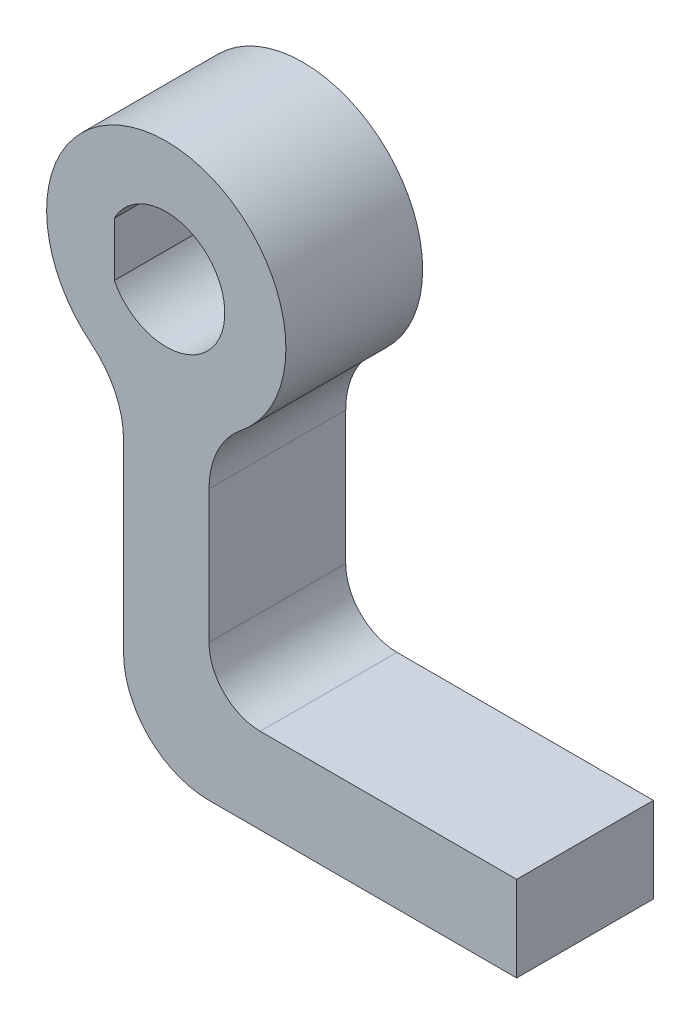
SolidWorks part; units mm, degrees
ref_plane "Front Plane" through (0, 0, 0) normal (0, 0, 1) x (1, 0, 0)
ref_plane "Top Plane" through (0, 0, 0) normal (0, 1, 0) x (1, 0, 0)
ref_plane "Right Plane" through (0, 0, 0) normal (1, 0, 0) x (0, 0, -1)
sketch "Sketch1" plane through (0, 0, 0) normal (0, 0, 1) x (1, 0, 0)
  line L0 (-2.5, -9.3675) -> (-2.5, -20.15)
  line L1 (2.5, -25.15) -> (20.5, -25.15)
  line L2 (20.5, -25.15) -> (20.5, -20.15)
  line L3 (20.5, -20.15) -> (5.5, -20.15)
  line L4 (2.5, -17.15) -> (2.5, -9.3675)
  line L5 (2.5, -8.6487) -> (-2.5, -8.6487) construction
  line L6 (0, -8.6487) -> (0, 0) construction
  line L7 (-3.04, 1.5777) -> (-3.04, -1.5777)
  arc A0 (-3.04, -1.5777) -> (-3.04, 1.5777) centre (0, 0) ccw
  arc A1 (4.375, -5.4644) -> (-4.375, -5.4644) centre (0, 0) ccw
  arc A2 (5.5, -20.15) -> (2.5, -17.15) centre (5.5, -17.15) cw
  arc A3 (2.5, -25.15) -> (-2.5, -20.15) centre (2.5, -20.15) cw
  arc A4 (-2.5, -9.3675) -> (-4.375, -5.4644) centre (-7.5, -9.3675) ccw
  arc A5 (2.5, -9.3675) -> (4.375, -5.4644) centre (7.5, -9.3675) cw
  point P18 (-2.5, -6.5383)
  point P21 (2.5, -6.5383)
  dimension "D1" = 3
  dimension "D2" = 6.85
  dimension "D3" = 5
  dimension "D7" = 5
  dimension "D6" = 20.15
  dimension "D8" = 14
  dimension "D9" = 5
  dimension "D4" = 5
  dimension "D5" = 23
  dimension "D10" = 3.04
extrude "Boss-Extrude1" add sketch "Sketch1" along normal mid plane 8
